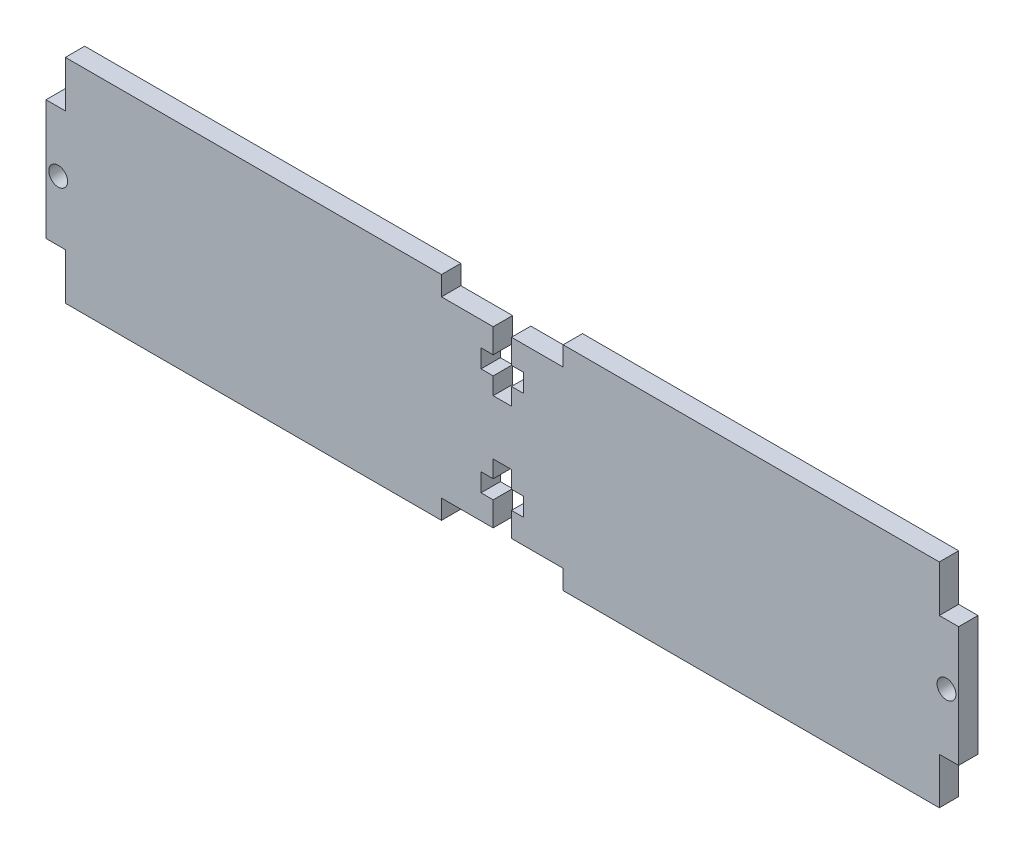
SolidWorks part; units mm, degrees
ref_plane "Front Plane" through (0, 0, 0) normal (0, 0, 1) x (1, 0, 0)
ref_plane "Top Plane" through (0, 0, 0) normal (0, 1, 0) x (1, 0, 0)
ref_plane "Right Plane" through (0, 0, 0) normal (1, 0, 0) x (0, 0, -1)
sketch "Sketch1" plane through (0, 0, 0) normal (0, 0, 1) x (1, 0, 0)
  line L0 (0, 17.5) -> (0, -17.5) construction
  line L1 (-75, 17.5) -> (75, 17.5)
  line L2 (-75, 17.5) -> (-75, -17.5)
  line L3 (-75, -17.5) -> (75, -17.5)
  line L4 (75, 17.5) -> (75, -17.5)
  line L5 (-75, 0) -> (75, 0) construction
  dimension "D1" = 150
  dimension "D2" = 35
extrude "Boss-Extrude1" add sketch "Sketch1" along normal blind 3.18
sketch "Sketch2" plane through (0, 0, 3.18) normal (0, 0, 1) x (1, 0, 0)
  line L0 (0, 17.5) -> (0, -17.5) construction
  line L1 (75, 17.5) -> (-75, 17.5) construction
  line L2 (-75, -17.5) -> (75, -17.5) construction
  line L3 (-75, 0) -> (75, 0) construction
  line L4 (-75, 17.5) -> (-75, -17.5) construction
  line L5 (75, -17.5) -> (75, 17.5) construction
  line L6 (1.5, 14.32) -> (10, 14.32)
  line L7 (-10, 17.5) -> (10, 17.5)
  line L8 (-10, 17.5) -> (-10, 14.32)
  line L9 (-10, 14.32) -> (-1.5, 14.32)
  line L10 (10, 17.5) -> (10, 14.32)
  line L12 (-1.5, 14.32) -> (-1.5, 10.32)
  line L13 (-1.5, 4.5) -> (1.5, 4.5)
  line L14 (1.5, 14.32) -> (1.5, 10.32)
  line L15 (-3.5, 10.32) -> (-1.5, 10.32)
  line L16 (-3.5, 10.32) -> (-3.5, 7.32)
  line L17 (-3.5, 7.32) -> (-1.5, 7.32)
  line L18 (3.5, 10.32) -> (3.5, 7.32)
  line L19 (1.5, 10.32) -> (3.5, 10.32)
  line L20 (-1.5, 7.32) -> (-1.5, 4.5)
  line L21 (1.5, 7.32) -> (3.5, 7.32)
  line L22 (1.5, 7.32) -> (1.5, 4.5)
  line L23 (-1.5, -7.32) -> (-1.5, -4.5)
  line L24 (1.5, -7.32) -> (1.5, -4.5)
  line L25 (-1.5, -4.5) -> (1.5, -4.5)
  line L26 (1.5, -7.32) -> (3.5, -7.32)
  line L27 (-3.5, -7.32) -> (-1.5, -7.32)
  line L28 (-3.5, -10.32) -> (-3.5, -7.32)
  line L29 (3.5, -10.32) -> (3.5, -7.32)
  line L30 (1.5, -10.32) -> (3.5, -10.32)
  line L31 (-3.5, -10.32) -> (-1.5, -10.32)
  line L32 (1.5, -14.32) -> (1.5, -10.32)
  line L33 (-1.5, -14.32) -> (-1.5, -10.32)
  line L34 (-10, -17.5) -> (-10, -14.32)
  line L35 (-10, -14.32) -> (-1.5, -14.32)
  line L36 (1.5, -14.32) -> (10, -14.32)
  line L37 (10, -17.5) -> (10, -14.32)
  line L38 (-10, -17.5) -> (10, -17.5)
  line L39 (75, -17.5) -> (71.82, -17.5)
  line L40 (-71.82, 17.5) -> (-75, 17.5)
  line L41 (-71.82, 17.5) -> (-71.82, 9.875)
  line L42 (-71.82, 9.875) -> (-75, 9.875)
  line L43 (-75, 17.5) -> (-75, 9.875)
  line L44 (-75, -9.875) -> (-71.82, -9.875)
  line L45 (-75, -9.875) -> (-75, -17.5)
  line L46 (-75, -17.5) -> (-71.82, -17.5)
  line L47 (-71.82, -9.875) -> (-71.82, -17.5)
  line L48 (75, -9.875) -> (75, -17.5)
  line L49 (71.82, -9.875) -> (71.82, -17.5)
  line L50 (75, -9.875) -> (71.82, -9.875)
  line L51 (71.82, 17.5) -> (75, 17.5)
  line L52 (75, 17.5) -> (75, 9.875)
  line L53 (71.82, 17.5) -> (71.82, 9.875)
  line L54 (71.82, 9.875) -> (75, 9.875)
  circle A0 centre (-73, 0) radius 1.55
  circle A1 centre (73, 0) radius 1.55
  dimension "D11" = 2
  dimension "D12" = 3.1
  dimension "D1" = 20
  dimension "D2" = 3.18
  dimension "D3" = 4
  dimension "D4" = 3
  dimension "D5" = 7
  dimension "D6" = 3
  dimension "D7" = 13
  dimension "D8" = 9.875
  dimension "D9" = 9.875
  dimension "D10" = 3.18
extrude "Cut-Extrude1" cut sketch "Sketch2" against normal through all
